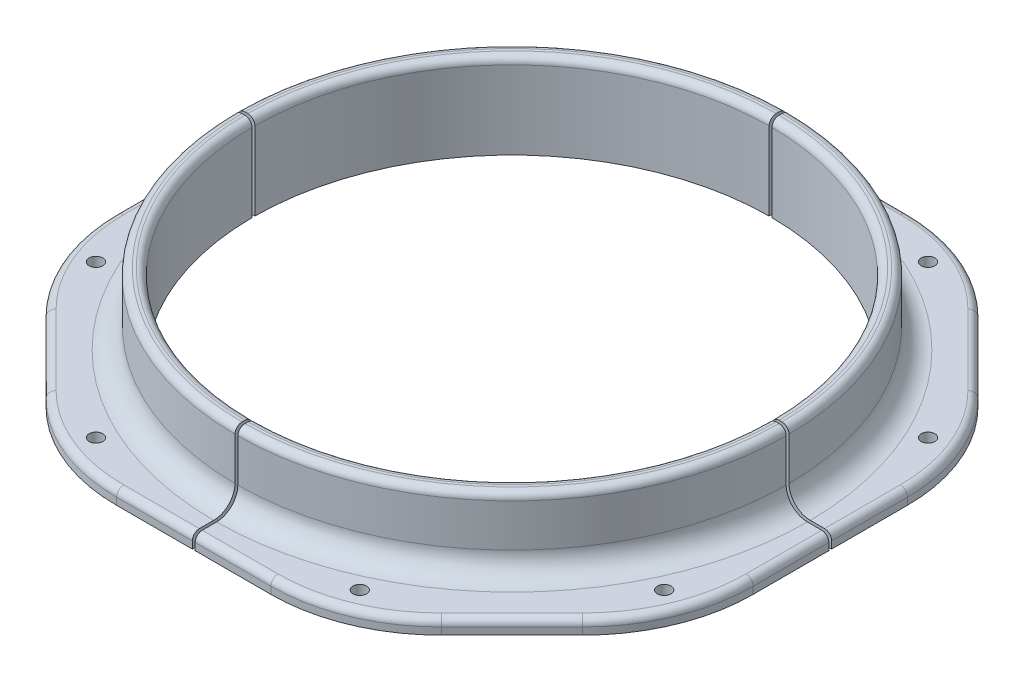
SolidWorks part; units mm, degrees
ref_plane "Front Plane" through (0, 0, 0) normal (0, 0, 1) x (1, 0, 0)
ref_plane "Top Plane" through (0, 0, 0) normal (0, 1, 0) x (1, 0, 0)
ref_plane "Right Plane" through (0, 0, 0) normal (1, 0, 0) x (0, 0, -1)
sketch "Sketch1" plane through (0, 0, 0) normal (0, 1, 0) x (1, 0, 0)
  circle A0 centre (0, 0) radius 115.57
  circle A1 centre (0, 0) radius 123.19
  dimension "D1" = 231.14
  dimension "D2" = 7.62
extrude "Boss-Extrude1" add sketch "Sketch1" along normal blind 38.1
sketch "Sketch2" plane through (0, 0, 0) normal (0, -1, 0) x (1, 0, 0)
  line L0 (0, 123.19) -> (0, 142.24) construction
  line L1 (-142.24, -142.24) -> (142.24, -142.24)
  line L2 (-142.24, -142.24) -> (-142.24, 142.24)
  line L3 (-142.24, 142.24) -> (142.24, 142.24)
  line L4 (142.24, -142.24) -> (142.24, 142.24)
  line L5 (-142.24, -142.24) -> (142.24, 142.24) construction
  line L6 (-142.24, 142.24) -> (142.24, -142.24) construction
  circle A0 centre (0, 0) radius 123.19 construction
  circle A1 centre (0, 0) radius 123.19
  dimension "D1" = 19.05
extrude "Boss-Extrude2" add sketch "Sketch2" against normal blind 6.35
chamfer "Chamfer1" distance 76.2 angle 45 4 edges at (-142.24, 3.175, -142.24) (142.24, 3.175, -142.24) (142.24, 3.175, 142.24) (-142.24, 3.175, 142.24)
sketch "Sketch3" plane through (0, 6.35, 0) normal (0, 1, 0) x (1, 0, 0)
  line L0 (66.04, -142.24) -> (51.8767, -111.7344) construction
  line L1 (142.24, -66.04) -> (111.7344, -51.8767) construction
  line L2 (111.7344, -51.8767) -> (0, 0) construction
  line L3 (0, 0) -> (51.8767, -111.7344) construction
  circle A0 centre (0, 0) radius 123.19 construction
  circle A2 centre (58.9584, -126.9872) radius 3.048
  circle A3 centre (126.9872, -58.9584) radius 3.048
  dimension "D1" = 6.096
extrude "Cut-Extrude1" cut sketch "Sketch3" against normal through all
pattern_circular "CirPattern1" count 4 over 360 about axis through (0, 0, 0) along (0, 1, 0) of "Cut-Extrude1"
fillet "Fillet1" radius 9.525 1 edges at (0, 6.35, -123.19)
fillet "Fillet2" radius 76.2 8 edges at (-142.24, 3.175, -66.04) (-66.04, 3.175, -142.24) (66.04, 3.175, -142.24) (142.24, 3.175, -66.04) (142.24, 3.175, 66.04) (66.04, 3.175, 142.24) (-66.04, 3.175, 142.24) (-142.24, 3.175, 66.04)
fillet "Fillet3" radius 3.175 2 edges at (0, 38.1, 115.57) (0, 38.1, 123.19)
fillet "Fillet4" radius 3.175 16 edges at (-136.4396, 6.35, 63.6374) (-142.24, 6.35, 0) (-136.4396, 6.35, -63.6374) (-104.14, 6.35, -104.14) (-63.6374, 6.35, -136.4396) (0, 6.35, -142.24) (63.6374, 6.35, -136.4396) (104.14, 6.35, -104.14) (136.4396, 6.35, -63.6374) (142.24, 6.35, 0) (136.4396, 6.35, 63.6374) (104.14, 6.35, 104.14) (63.6374, 6.35, 136.4396) (0, 6.35, 142.24) (-63.6374, 6.35, 136.4396) (-104.14, 6.35, 104.14)
sketch "Sketch4" plane through (0, 0, 0) normal (0, -1, 0) x (1, 0, 0)
  line L0 (0, -187.1717) -> (0, 187.1717) construction
  line L1 (0.635, -171.6047) -> (0.635, -0.635)
  line L2 (-0.635, -171.6047) -> (-0.635, -0.635)
  line L3 (-0.635, 187.1717) -> (0.635, 187.1717)
  line L5 (0.635, -165.1139) -> (0.635, 165.1139) construction
  line L6 (-0.635, -171.6047) -> (0.635, -171.6047)
  line L8 (-167.9748, -0.635) -> (-0.635, -0.635)
  line L15 (194.3679, -0.635) -> (194.3679, 0.635)
  line L16 (194.3679, 0.635) -> (0.635, 0.635)
  line L17 (-167.9748, 0.635) -> (-167.9748, -0.635)
  line L18 (0, 0) -> (-167.9748, 0) construction
  line L19 (-0.635, -0.635) -> (-0.635, 0) construction
  line L20 (-0.635, 0.635) -> (-0.635, 187.1717)
  line L21 (-0.635, -0.635) -> (0, -0.635) construction
  line L22 (0.635, -0.635) -> (194.3679, -0.635)
  line L23 (0, -0.635) -> (0.635, -0.635) construction
  line L24 (0.635, -0.635) -> (0.635, 0.635) construction
  line L25 (0.635, 0.635) -> (0.635, 187.1717)
  line L26 (0.635, 0.635) -> (0, 0.635) construction
  line L27 (-0.635, 0.635) -> (-167.9748, 0.635)
  line L28 (0, 0.635) -> (-0.635, 0.635) construction
  line L29 (-0.635, 0) -> (-0.635, 0.635) construction
  line L30 (0, -165.1139) -> (0, 165.1139) construction
  point P3 (0, 160.5916)
  point P4 (0, 0)
  point P13 (0.635, -155.3552)
  point P14 (0, 0)
  point P18 (0, 0)
  point P19 (0, 0)
  point P20 (0, 0)
  point P31 (0, 0)
  point P32 (0, 187.1717)
  dimension "D2" = 0.635
  dimension "D3" = 1.27
  dimension "D1" = 0.635
extrude "Cut-Extrude2" cut sketch "Sketch4" against normal through all
